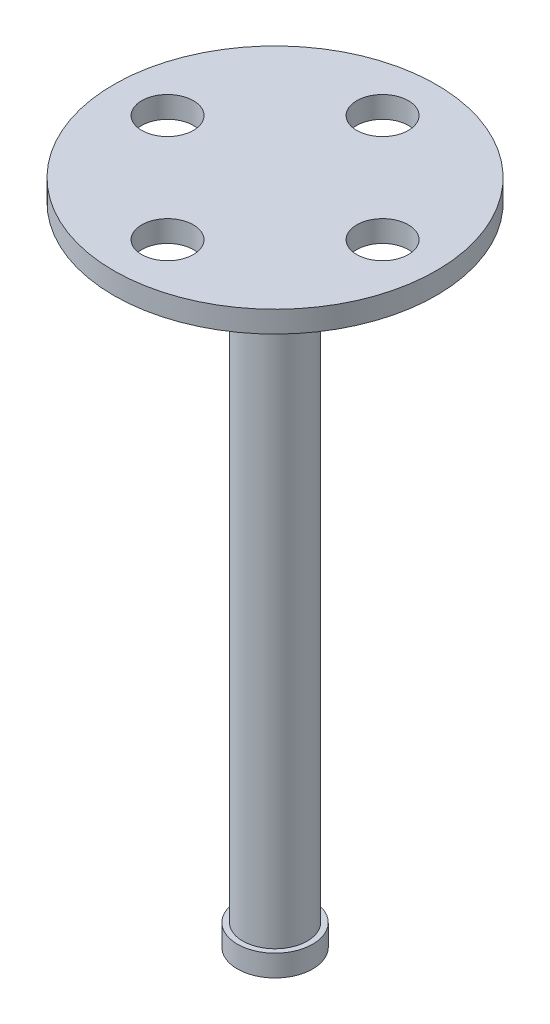
SolidWorks part; units mm, degrees
ref_plane "前视基准面" through (0, 0, 0) normal (0, 0, 1) x (1, 0, 0)
ref_plane "上视基准面" through (0, 0, 0) normal (0, 1, 0) x (1, 0, 0)
ref_plane "右视基准面" through (0, 0, 0) normal (1, 0, 0) x (0, 0, -1)
sketch "草图1" plane through (0, 0, 0) normal (0, 1, 0) x (1, 0, 0)
  circle A0 centre (0, 0) radius 17.5
  dimension "D1" = 35
extrude "凸台-拉伸1" add sketch "草图1" along normal blind 10
sketch "草图2" plane through (0, 0, 0) normal (0, 1, 0) x (1, 0, 0)
  circle A0 centre (0, 0) radius 15
  dimension "D1" = 30
extrude "凸台-拉伸2" add sketch "草图2" along normal blind 300
sketch "草图3" plane through (0, 300, 0) normal (0, 1, 0) x (1, 0, 0)
  circle A0 centre (0, 0) radius 75
  dimension "D1" = 150
extrude "凸台-拉伸3" add sketch "草图3" along normal blind 10
fillet "圆角1" radius 10 1 edges at (0, 300, 15)
sketch "草图4" plane through (0, 310, 0) normal (0, 1, 0) x (1, 0, 0)
  circle A0 centre (0, 0) radius 50 construction
  point P3 (50, 0)
  point P4 (50, 0)
  point P7 (0, -50)
  point P8 (-50, 0)
  point P9 (0, 50)
  dimension "D1" = 100
  dimension "D2" = 4
hole_wizard "孔1" positions "草图4" profile "草图5" legacy end condition up to next
sketch "草图5" plane through (0, 310, -50) normal (1, 0, 0) x (0, 0, 1)
  line L0 (0, 0) -> (0, 10)
  line L1 (0, 10) -> (12, 10)
  line L2 (12, 10) -> (12, 0)
  line L3 (12, 0) -> (0, 0)
  line L4 (0, 110) -> (0, -10) construction
  dimension "直径" = 24
  dimension "深度" = 10
